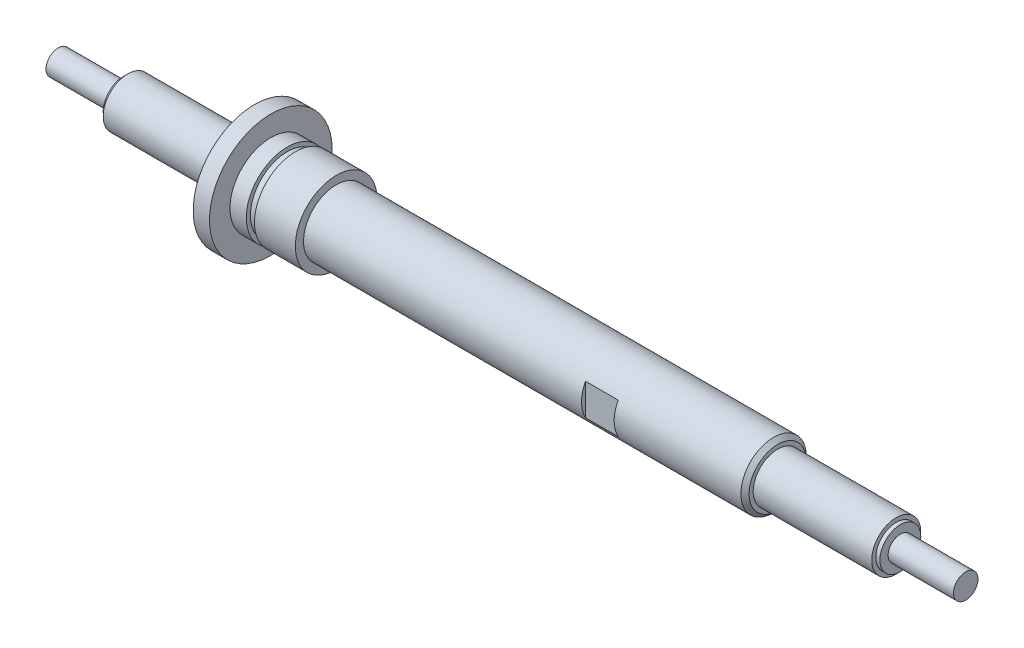
SolidWorks part; units mm, degrees
ref_plane "前视基准面" through (0, 0, 0) normal (0, 0, 1) x (1, 0, 0)
ref_plane "上视基准面" through (0, 0, 0) normal (0, 1, 0) x (1, 0, 0)
ref_plane "右视基准面" through (0, 0, 0) normal (1, 0, 0) x (0, 0, -1)
sketch "草图1" plane through (0, 0, 0) normal (1, 0, 0) x (0, 0, -1)
  circle A0 centre (0, 0) radius 4
  dimension "D1" = 8
extrude "凸台-拉伸1" add sketch "草图1" along normal blind 1
sketch "草图2" plane through (0, 0, 0) normal (-1, 0, 0) x (0, 0, 1)
  circle A0 centre (0, 0) radius 3
  dimension "D1" = 6
extrude "凸台-拉伸2" add sketch "草图2" along normal blind 6
sketch "草图3" plane through (-6, 0, 0) normal (-1, 0, 0) x (0, 0, 1)
  circle A0 centre (0, 0) radius 3
  dimension "D1" = 6
extrude "凸台-拉伸3" add sketch "草图3" along normal blind 17
sketch "草图4" plane through (1, 0, 0) normal (1, 0, 0) x (0, 0, -1)
  circle A0 centre (0, 0) radius 7.5
  dimension "D1" = 15
extrude "凸台-拉伸4" add sketch "草图4" along normal blind 2
sketch "草图5" plane through (3, 0, 0) normal (1, 0, 0) x (0, 0, -1)
  circle A0 centre (0, 0) radius 5
  dimension "D1" = 10
extrude "凸台-拉伸5" add sketch "草图5" along normal blind 8
cosmetic thread "装饰螺纹线2" parameters "D1"=5, "D2"=10
cosmetic thread "装饰螺纹线3" parameters "D1"=5, "D2"=9
cosmetic thread "装饰螺纹线4" parameters "D1"=5.2, "D2"=9
sketch "草图6" plane through (11, 0, 0) normal (1, 0, 0) x (0, 0, -1)
  circle A0 centre (0, 0) radius 4
  dimension "D1" = 8
extrude "凸台-拉伸6" add sketch "草图6" along normal blind 54
sketch "草图7" plane through (65, 0, 0) normal (1, 0, 0) x (0, 0, -1)
  circle A0 centre (0, 0) radius 3
  dimension "D1" = 6
extrude "凸台-拉伸7" add sketch "草图7" along normal blind 6
sketch "草图8" plane through (71, 0, 0) normal (1, 0, 0) x (0, 0, -1)
  circle A0 centre (0, 0) radius 3
  dimension "D1" = 6
extrude "凸台-拉伸8" add sketch "草图8" along normal blind 17
chamfer "倒角1" distance 0.5 angle 45 1 edges at (65, 0, -4)
chamfer "倒角2" distance 0.5 angle 45 1 edges at (0, 0, -4)
sketch "草图11" plane through (3, 0, 0) normal (1, 0, 0) x (0, 0, -1)
  circle A0 centre (0, 0) radius 4.5
  circle A1 centre (0, 0) radius 5
  dimension "D1" = 9
  dimension "D2" = 10
extrude "切除-拉伸2" cut sketch "草图11" along normal blind 1 from offset 2
sketch "草图12" plane through (0, 0, 0) normal (0, 1, 0) x (1, 0, 0)
  line L0 (64.5, 4) -> (11, 4) construction
  line L1 (45, 4) -> (49, 4)
  line L2 (45, 4) -> (45, 3.5)
  line L3 (45, 3.5) -> (49, 3.5)
  line L4 (49, 4) -> (49, 3.5)
  line L5 (65, 0) -> (50.1879, 0) construction
  line L6 (65, -3) -> (65, 3) construction
  line L7 (65, -3.5) -> (65, 3.5) construction
  line L8 (49, -4) -> (49, -3.5)
  line L9 (45, -3.5) -> (49, -3.5)
  line L10 (45, -4) -> (49, -4)
  line L11 (45, -4) -> (45, -3.5)
  dimension "D1" = 20
  dimension "D2" = 4
  dimension "D3" = 7
extrude "切除-拉伸3" cut sketch "草图12" against normal mid plane 10
sketch "草图14" plane through (88, 0, 0) normal (1, 0, 0) x (0, 0, -1)
  circle A0 centre (0, 0) radius 3
  circle A1 centre (0, 0) radius 1.5
  dimension "D1" = 6
  dimension "D2" = 3
extrude "切除-拉伸5" cut sketch "草图14" against normal blind 8
cosmetic thread "装饰螺纹线5" parameters "D1"=4, "D2"=2
ref_plane "基准面1" through (32.5, 0, 0) normal (1, 0, 0) x (0, 0, -1)
sketch "草图15" plane through (80, 0, 0) normal (1, 0, 0) x (0, 0, -1)
  circle A0 centre (0, 0) radius 2.5
  circle A1 centre (0, 0) radius 3
  dimension "D1" = 5
  dimension "D2" = 6
extrude "切除-拉伸6" cut sketch "草图15" against normal blind 0.5
mirror "镜向2" about plane through (32.5, 0, 0) normal (1, 0, 0) of "切除-拉伸5", "切除-拉伸6"
